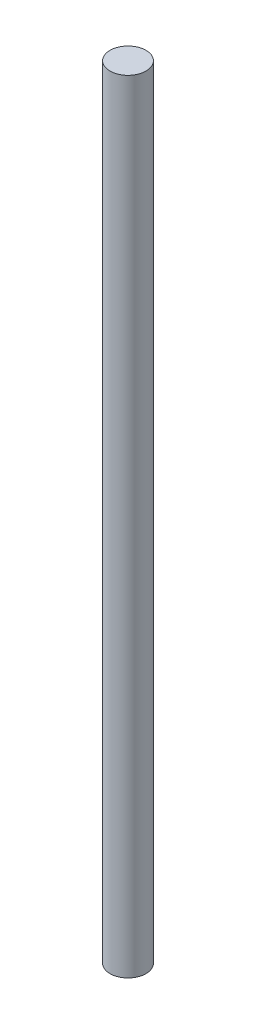
SolidWorks part; units mm, degrees
ref_plane "Front Plane" through (0, 0, 0) normal (0, 0, 1) x (1, 0, 0)
ref_plane "Top Plane" through (0, 0, 0) normal (0, 1, 0) x (1, 0, 0)
ref_plane "Right Plane" through (0, 0, 0) normal (1, 0, 0) x (0, 0, -1)
sketch "Sketch1" plane through (0, 0, 0) normal (0, 1, 0) x (1, 0, 0)
  circle A0 centre (0, 0) radius 1.7526
  dimension "D1" = 3.5052
extrude "Boss-Extrude1" add sketch "Sketch1" along normal blind 76.2
cosmetic thread "Cosmetic Thread1" parameters "D1"=5, "D2"=2.5603
